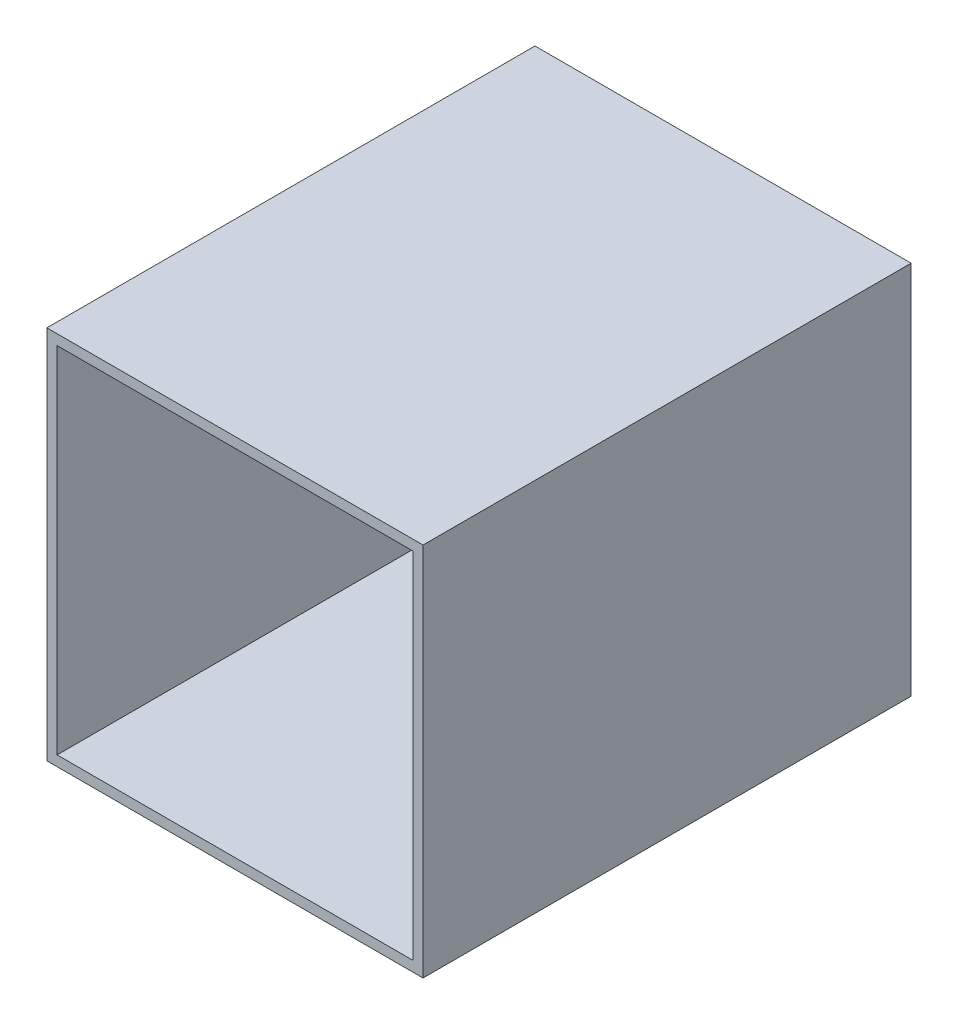
SolidWorks part; units mm, degrees
ref_plane "Alzado" through (0, 0, 0) normal (0, 0, 1) x (1, 0, 0)
ref_plane "Planta" through (0, 0, 0) normal (0, 1, 0) x (1, 0, 0)
ref_plane "Vista lateral" through (0, 0, 0) normal (1, 0, 0) x (0, 0, -1)
sketch "Croquis1" plane through (0, 0, 0) normal (0, 0, 1) x (1, 0, 0)
  line L0 (-74.5, 74.25) -> (-74.5, -74.25)
  line L1 (-78.8, 78.55) -> (78.8, 78.55)
  line L2 (-78.8, 78.55) -> (-78.8, -78.55)
  line L3 (-78.8, -78.55) -> (78.8, -78.55)
  line L4 (78.8, 78.55) -> (78.8, -78.55)
  line L5 (-78.8, 78.55) -> (78.8, -78.55) construction
  line L6 (-78.8, -78.55) -> (78.8, 78.55) construction
  line L7 (-74.5, -74.25) -> (74.5, -74.25)
  line L8 (74.5, 74.25) -> (74.5, -74.25)
  line L9 (-74.5, 74.25) -> (74.5, 74.25)
  point P0 (0, 0)
  dimension "D1" = 157.6
  dimension "D2" = 157.1
  dimension "D3" = 4.3
extrude "Saliente-Extruir1" add sketch "Croquis1" along normal blind 204.5
sketch "Croquis2" plane through (-74.5, 0, 0) normal (1, 0, 0) x (0, 0, -1)
  line L0 (-204.5, -78.55) -> (0, -78.55) construction
  line L1 (0, 78.55) -> (-4, 78.55)
  line L2 (0, 78.55) -> (0, -78.55)
  line L3 (0, -78.55) -> (-4, -78.55)
  line L4 (-4, 78.55) -> (-4, -78.55)
  dimension "D1" = 4
extrude "Saliente-Extruir2" add sketch "Croquis2" along normal up to surface (149 mm away) up to face at (74.5, 0, 102.25)
sketch "Croquis3" plane through (0, -78.55, 0) normal (0, -1, 0) x (1, 0, 0)
  line L0 (74.5, 4) -> (-74.5, 4) construction
  circle A0 centre (0, 34) radius 29.5 construction
  circle A1 centre (0, 34) radius 11
  dimension "D1" = 59
  dimension "D2" = 30
  dimension "D3" = 22
extrude "Cortar-Extruir1" cut sketch "Croquis3" against normal up to surface (4.3 mm away) up to face at (0, -74.25, 104.25)
